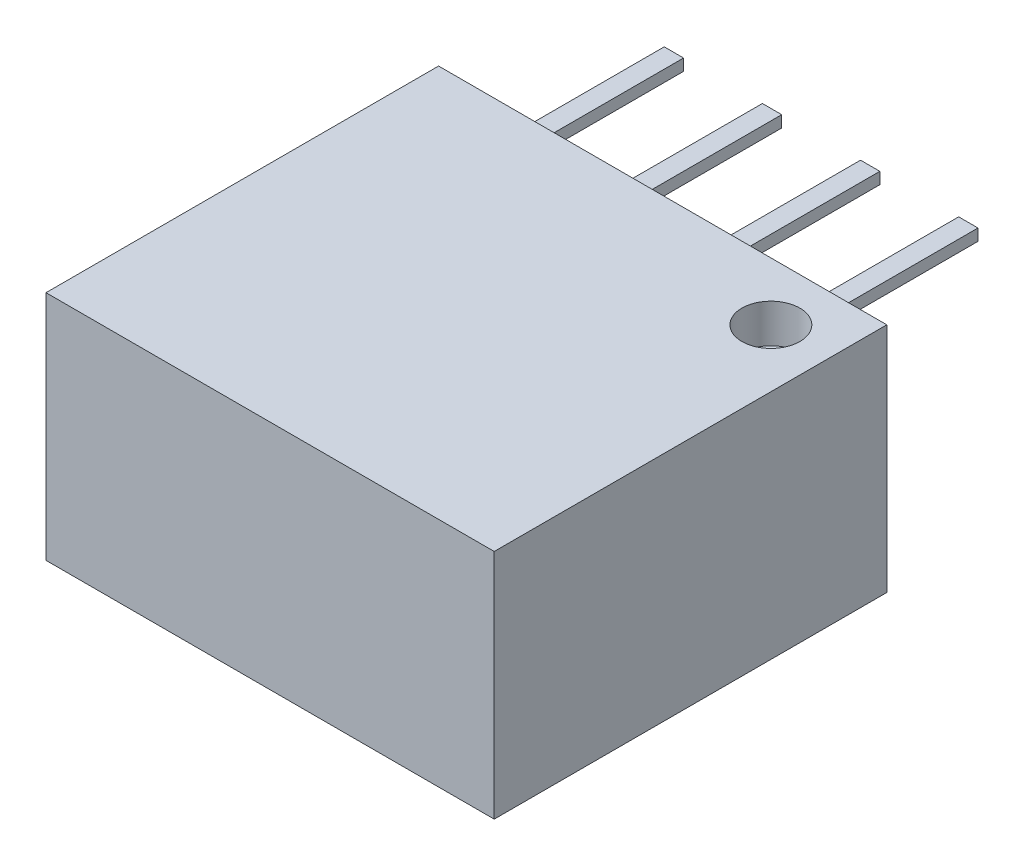
SolidWorks part; units mm, degrees
ref_plane "前视基准面" through (0, 0, 0) normal (0, 0, 1) x (1, 0, 0)
ref_plane "上视基准面" through (0, 0, 0) normal (0, 1, 0) x (1, 0, 0)
ref_plane "右视基准面" through (0, 0, 0) normal (1, 0, 0) x (0, 0, -1)
sketch "草图1" plane through (0, 0, 0) normal (0, 0, 1) x (1, 0, 0)
  line L1 (-5.8, -3) -> (5.8, -3)
  line L2 (-5.8, -3) -> (-5.8, 3)
  line L3 (-5.8, 3) -> (5.8, 3)
  line L4 (5.8, -3) -> (5.8, 3)
  line L5 (-5.8, -3) -> (5.8, 3) construction
  line L6 (-5.8, 3) -> (5.8, -3) construction
  point P0 (0, 0)
  dimension "D1" = 6
  dimension "D2" = 11.6
extrude "凸台-拉伸1" add sketch "草图1" along normal blind 10.16
sketch "草图2" plane through (0, 0, 0) normal (0, 0, -1) x (-1, 0, 0)
  line L0 (-5.8, 3) -> (5.8, 3) construction
  line L1 (-1.52, 1.95) -> (-1.52, 2.25)
  line L2 (-4.06, 1.95) -> (-3.56, 1.95)
  line L3 (-4.06, 1.95) -> (-4.06, 2.25)
  line L4 (1.27, 2.1) -> (-1.27, 2.1) construction
  line L5 (-1.27, 2.1) -> (-3.81, 2.1) construction
  line L6 (1.27, 2.1) -> (3.81, 2.1) construction
  line L7 (-4.06, 2.25) -> (-3.56, 2.25)
  line L8 (-3.56, 1.95) -> (-3.56, 2.25)
  line L9 (-4.06, 1.95) -> (-3.56, 2.25) construction
  line L10 (-4.06, 2.25) -> (-3.56, 1.95) construction
  line L11 (-1.52, 1.95) -> (-1.02, 1.95)
  line L12 (-1.02, 1.95) -> (-1.02, 2.25)
  line L13 (-1.52, 2.25) -> (-1.02, 2.25)
  line L14 (1.02, 1.95) -> (1.02, 2.25)
  line L15 (1.02, 1.95) -> (1.52, 1.95)
  line L16 (1.52, 1.95) -> (1.52, 2.25)
  line L17 (1.02, 2.25) -> (1.52, 2.25)
  line L18 (3.56, 1.95) -> (3.56, 2.25)
  line L19 (3.56, 1.95) -> (4.06, 1.95)
  line L20 (4.06, 1.95) -> (4.06, 2.25)
  line L21 (3.56, 2.25) -> (4.06, 2.25)
  point P4 (0, 2.1)
  dimension "D3" = 4
  dimension "D1" = 0.9
  dimension "D2" = 2.54
  dimension "D4" = 2.54
  dimension "D7" = 2.54
  dimension "D9" = 0.3
  dimension "D10" = 0.5
extrude "凸台-拉伸2" add sketch "草图2" along normal blind 4.1 separate body
sketch "草图3" plane through (0, 3, 0) normal (0, 1, 0) x (1, 0, 0)
  line L0 (5.8, 0) -> (-5.8, 0) construction
  line L1 (5.8, -10.16) -> (5.8, 0) construction
  circle A0 centre (4.3, -1.5) radius 0.75
  dimension "D1" = 1.5
  dimension "D2" = 1.5
  dimension "D3" = 1.5
extrude "切除-拉伸1" cut sketch "草图3" against normal blind 1
